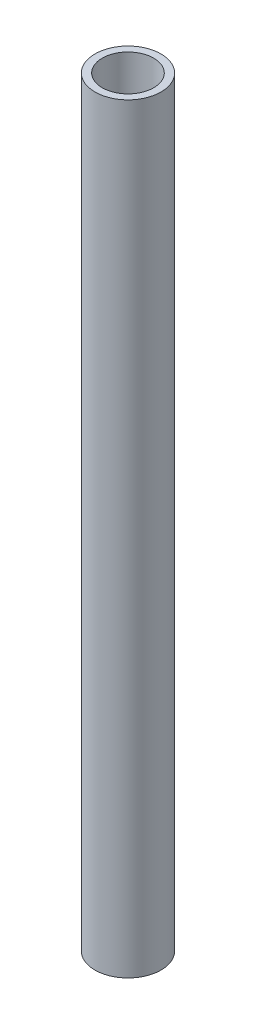
SolidWorks part; units mm, degrees
ref_plane "Front Plane" through (0, 0, 0) normal (0, 0, 1) x (1, 0, 0)
ref_plane "Top Plane" through (0, 0, 0) normal (0, 1, 0) x (1, 0, 0)
ref_plane "Right Plane" through (0, 0, 0) normal (1, 0, 0) x (0, 0, -1)
sketch "Sketch1" plane through (0, 0, 0) normal (0, 1, 0) x (1, 0, 0)
  circle A0 centre (0, 0) radius 10.85
  circle A1 centre (0, 0) radius 8.45
  dimension "D1" = 16.9
  dimension "D2" = 21.7
extrude "Boss-Extrude1" add sketch "Sketch1" along normal blind 250
